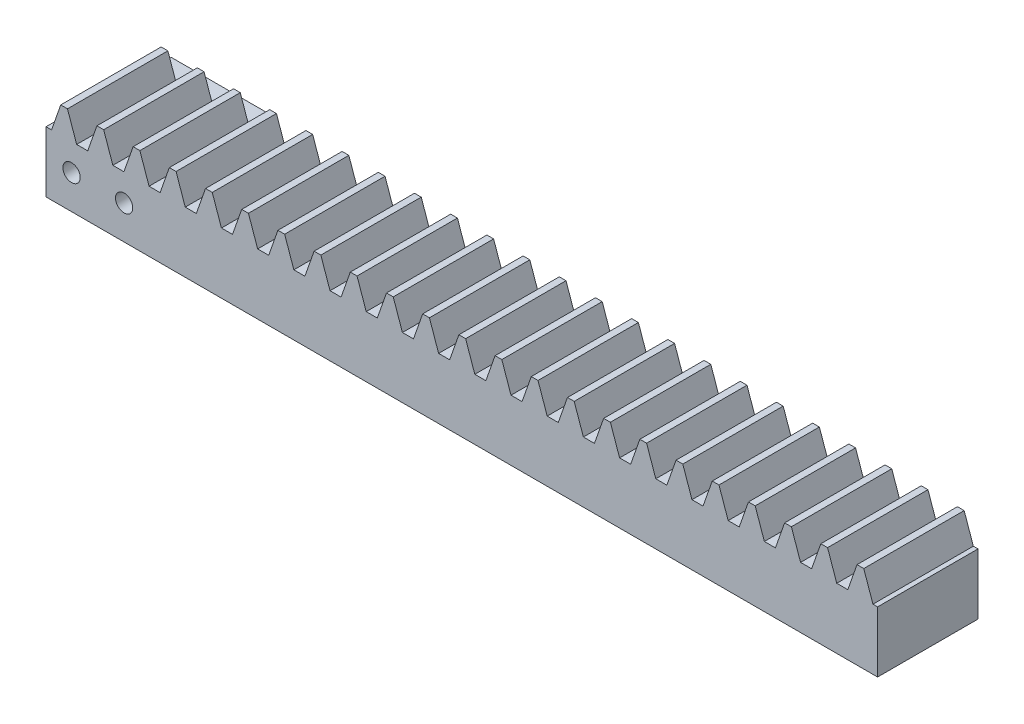
SolidWorks part; units mm, degrees
ref_plane "Alzado" through (0, 0, 0) normal (0, 0, 1) x (1, 0, 0)
ref_plane "Planta" through (0, 0, 0) normal (0, 1, 0) x (1, 0, 0)
ref_plane "Vista lateral" through (0, 0, 0) normal (1, 0, 0) x (0, 0, -1)
sketch "Croquis1" plane through (0, 0, 0) normal (0, 0, 1) x (1, 0, 0)
  line L0 (0, 0) -> (-281.0462, 0) construction
  line L2 (99.7585, -7.9375) -> (-99.7585, -7.9375)
  line L3 (99.7585, -7.9375) -> (99.7585, 7.9375)
  line L4 (99.7585, 7.9375) -> (-99.7585, 7.9375)
  line L5 (-99.7585, -7.9375) -> (-99.7585, 7.9375)
  line L6 (99.7585, -7.9375) -> (-99.7585, 7.9375) construction
  line L7 (99.7585, 7.9375) -> (-99.7585, -7.9375) construction
  point P3 (0, 0)
  dimension "D1" = 15.875
  dimension "D2" = 199.517
extrude "Saliente-Extruir1" add sketch "Croquis1" along normal blind 18.446
sketch "Croquis2" plane through (0, 0, 18.446) normal (0, 0, 1) x (1, 0, 0)
  line L0 (-99.7585, 5.8217) -> (-50099.7585, 5.8217) construction
  line L2 (99.7585, 7.9375) -> (-99.7585, 7.9375) construction
  line L6 (-99.7585, 7.9375) -> (-99.7585, -7.9375) construction
  line L10 (-99.7585, 5.2921) -> (-99.7585, 50005.2921) construction
  dimension "D1" = 2.1158
sketch "Croquis4" plane through (0, 0, 18.446) normal (0, 0, 1) x (1, 0, 0)
  line L0 (-99.7585, -0.0793) -> (-99.7585, 49999.9207) construction
  line L1 (-99.7585, 7.9375) -> (-99.7585, -7.9375) construction
  line L2 (-98.7425, 3.1115) -> (-100.7745, 3.1115)
  line L3 (-97.0534, 7.9375) -> (-102.4636, 7.9375)
  line L4 (99.7585, 7.9375) -> (-99.7585, 7.9375) construction
  line L5 (-100.7745, 3.1115) -> (-102.4636, 7.9375)
  line L6 (-98.7425, 3.1115) -> (-97.0534, 7.9375)
  line L8 (-101.6635, 5.6515) -> (-97.8535, 5.6515) construction
  line L9 (-101.6635, 5.6515) -> (-101.6635, 10.7315) construction
  line L10 (-101.6635, 10.7315) -> (-97.8535, 10.7315) construction
  line L11 (-97.8535, 5.6515) -> (-97.8535, 10.7315) construction
  point P4 (-99.7585, 0)
  point P8 (-99.7585, 3.1115)
  point P11 (-99.7585, 7.9375)
  dimension "D1" = 3.81
  dimension "D2" = 2.54
  dimension "D3" = 4.826
  dimension "D4" = 2.032
  dimension "D5" = 5.08
extrude "Cortar-Extruir3" cut sketch "Croquis4" against normal through all
pattern_linear "MatrizL1" count 32 spacing 6.6497 along (1, 0, 0) of "Cortar-Extruir3"
sketch "Croquis5" plane through (0, 0, 18.446) normal (0, 0, 1) x (1, 0, 0)
  line L0 (-99.7585, 3.1115) -> (-99.7585, -7.9375) construction
  line L1 (-99.7585, -6.3375) -> (-80.7085, -6.3375)
  line L2 (-99.7585, -6.3375) -> (-99.7585, 2.6545)
  line L3 (-99.7585, 2.6545) -> (-80.7085, 2.6545)
  line L4 (-80.7085, -6.3375) -> (-80.7085, 2.6545)
  line L5 (-99.7585, -7.9375) -> (99.7585, -7.9375) construction
  dimension "D1" = 1.6
  dimension "D2" = 8.992
  dimension "D3" = 19.05
extrude "Saliente-Extruir2" add sketch "Croquis5" against normal blind 23.002
sketch "Croquis6" plane through (0, 0, -4.556) normal (0, 0, -1) x (-1, 0, 0)
  line L0 (-99.7585, -1.8415) -> (-50099.7585, -1.8415) construction
  line L1 (99.7585, 2.6545) -> (99.7585, -6.3375) construction
  line L2 (90.2335, -1.7655) -> (90.2335, 49998.2345) construction
  line L3 (99.7585, 2.6545) -> (80.7085, 2.6545) construction
  circle A0 centre (85.4075, -1.8415) radius 1.5875
  circle A1 centre (95.0595, -1.8415) radius 1.5875
  point P4 (99.7585, -1.8415)
  point P15 (90.2335, 2.6545)
  dimension "D2" = 3.175
  dimension "D3" = 4.826
extrude "Cortar-Extruir4" cut sketch "Croquis6" against normal through all
scale "Escala1" scale about centroid uniform scaling yes scale factor 0.25
sketch "Croquis7" plane through (24.3621, 0, 0) normal (1, 0, 0) x (0, 0, -1)
  circle A0 centre (-9.1123, -1.4557) radius 4.214
extrude "Cortar-Extruir5" cut sketch "Croquis7" against normal blind 11.684
sketch "Croquis8" plane through (0, -2.894, 0) normal (0, -1, 0) x (1, 0, 0)
  line L1 (-25.5172, 6.7923) -> (12.6781, 6.7923)
  line L2 (-25.5172, 6.7923) -> (-25.5172, 11.4038)
  line L3 (-25.5172, 11.4038) -> (12.6781, 11.4038)
  line L4 (12.6781, 6.7923) -> (12.6781, 11.4038)
extrude "Saliente-Extruir3" add sketch "Croquis8" along normal blind 0.03
sketch "Sketch1" plane through (-25.5172, 0, 0) normal (-1, 0, 0) x (0, 0, 1)
  line L0 (6.7923, -0.1317) -> (11.4038, -0.1317) construction
  line L1 (11.4038, -0.1317) -> (11.4038, -2.924) construction
  point P0 (9.0981, -1.5279)
  point P1 (0, 0)
  point P4 (9.0981, -0.1317)
  point P5 (0, 0)
  point P8 (11.4038, -1.5279)
  point P9 (0, 0)
  point P10 (0, 0)
  point P11 (0, 0)
  point P12 (0, 0)
